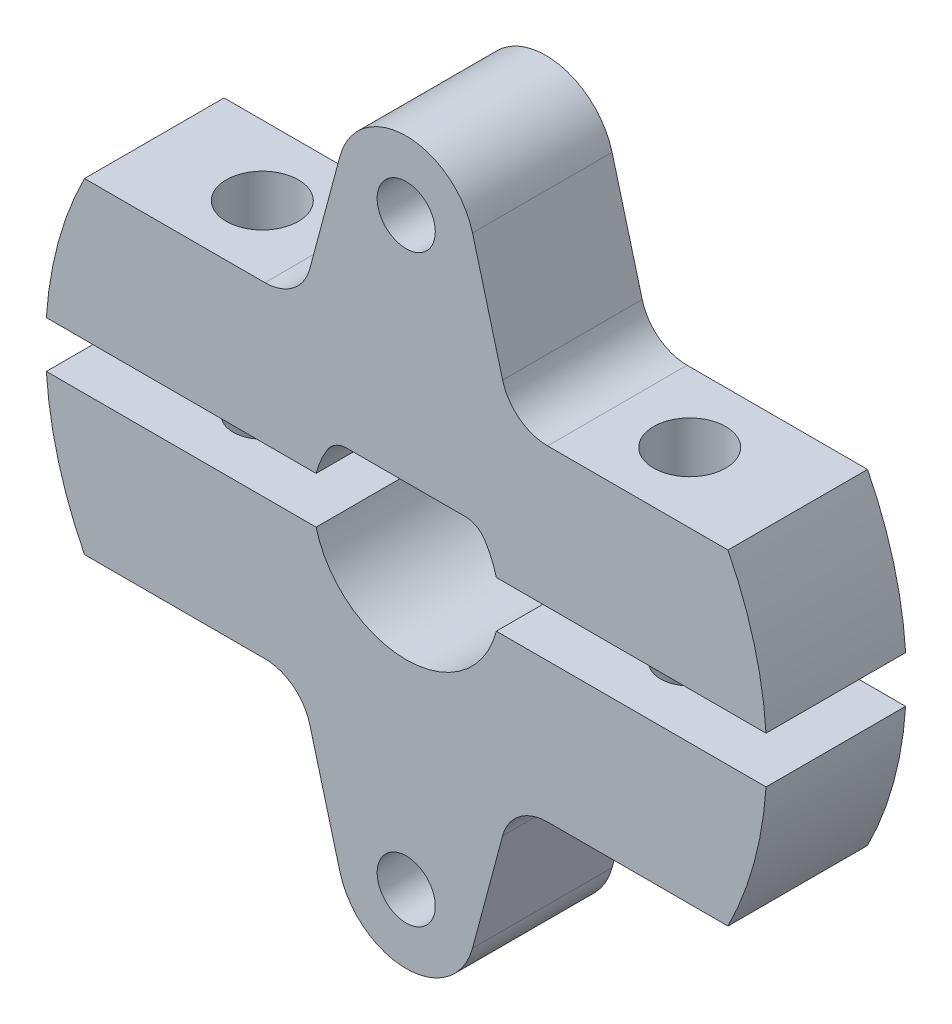
SolidWorks part; units mm, degrees
material "6061 合金"
ref_plane "前视基准面" through (0, 0, 0) normal (0, 0, 1) x (1, 0, 0)
ref_plane "上视基准面" through (0, 0, 0) normal (0, 1, 0) x (1, 0, 0)
ref_plane "右视基准面" through (0, 0, 0) normal (1, 0, 0) x (0, 0, -1)
sketch "草图1" plane through (0, 0, 0) normal (0, 0, 1) x (1, 0, 0)
  line L0 (-3.0397, 2.6) -> (3.0397, 2.6)
  arc A0 (-3.0397, 2.6) -> (3.0397, 2.6) centre (0, 0) ccw
  circle A1 centre (0, 0) radius 12.5 construction
  circle A3 centre (0, 0) radius 15.5
  dimension "D1" = 8
  dimension "D2" = 25
  dimension "D3" = 2.6
  dimension "D4" = 3
extrude "凸台-拉伸1" add sketch "草图1" along normal mid plane 6
sketch "草图2" plane through (0, 0, 3) normal (0, 0, 1) x (1, 0, 0)
  line L1 (-17.5, -1) -> (17.5, -1)
  line L2 (-17.5, -1) -> (-17.5, 1)
  line L3 (-17.5, 1) -> (17.5, 1)
  line L4 (17.5, -1) -> (17.5, 1)
  line L5 (0, 1) -> (0, -1) construction
  line L6 (-17.5, 0) -> (17.5, 0) construction
  point P0 (0, 0)
  dimension "D1" = 2
  dimension "D2" = 35
extrude "切除-拉伸1" cut sketch "草图2" against normal mid plane 48
sketch "草图3" plane through (0, 0, 3) normal (0, 0, 1) x (1, 0, 0)
  circle A0 centre (0, 0) radius 12.5 construction
  dimension "D1" = 25
hole_wizard "M3 螺纹孔1" positions "草图4" profile "草图5" tap size "M3" standard "GB" end condition through all
sketch "草图4" plane through (0, 0, 3) normal (0, 0, 1) x (1, 0, 0)
  line L0 (0, 12.55) -> (0, 0) construction
  point P0 (0, 12.55)
  dimension "D1" = 12.55
sketch "草图5" plane through (0, 12.55, 3) normal (1, 0, 0) x (0, -1, 0)
  line L0 (0, 0) -> (0, 6)
  line L1 (0, 6) -> (1.25, 6)
  line L2 (1.25, 6) -> (1.25, 0)
  line L5 (1.25, 0) -> (0, 0)
  line L11 (0, -6.35) -> (0, 107.95) construction
  dimension "通孔螺纹孔钻头直径" = 2.5
  dimension "通孔螺纹孔钻头深度" = 6
cosmetic thread "孔螺蚊线1" parameters "D2"=3
pattern_circular "阵列(圆周)1" count 2 over 360 about axis through (0, 0, 0) along (0, 0, 1) of "M3 螺纹孔1"
cosmetic thread "孔螺蚊线2" parameters "D2"=3
cosmetic thread "孔螺蚊线3" parameters "D2"=3
cosmetic thread "孔螺蚊线4" parameters "D2"=3
cosmetic thread "孔螺蚊线5" parameters "D2"=3
sketch "草图7" plane through (0, 0, 3) normal (0, 0, 1) x (1, 0, 0)
  line L0 (-13.8293, 7) -> (-4.5412, 7)
  line L1 (-4.5412, 7) -> (-2.8495, 13.3135)
  line L2 (-3.873, 1) -> (-15.4677, 1) construction
  line L3 (0, 12.55) -> (0, -12.55) construction
  line L4 (4.5412, 7) -> (2.8495, 13.3135)
  line L5 (13.8293, 7) -> (4.5412, 7)
  line L6 (0, 0) -> (15.5289, 0) construction
  line L7 (-4.5412, 7) -> (-2.8495, 13.3135)
  line L8 (4.5412, 7) -> (2.8495, 13.3135)
  line L9 (13.8293, 7) -> (4.5412, 7)
  line L10 (-13.8293, 7) -> (-4.5412, 7)
  line L11 (-13.8293, -7) -> (-4.5412, -7)
  line L12 (13.8293, -7) -> (4.5412, -7)
  line L13 (4.5412, -7) -> (2.8495, -13.3135)
  line L14 (-4.5412, -7) -> (-2.8495, -13.3135)
  line L15 (13.8293, -7) -> (4.5412, -7)
  line L16 (4.5412, -7) -> (2.8495, -13.3135)
  line L17 (-4.5412, -7) -> (-2.8495, -13.3135)
  line L18 (-13.8293, -7) -> (-4.5412, -7)
  arc A0 (2.8495, 13.3135) -> (-2.8495, 13.3135) centre (0, 12.55) ccw
  arc A1 (15.4677, 1) -> (-15.4677, 1) centre (0, 0) ccw construction
  arc A2 (13.8293, 7) -> (-13.8293, 7) centre (0, 0) ccw
  arc A3 (13.8293, -7) -> (-13.8293, -7) centre (0, 0) cw
  arc A4 (2.8495, -13.3135) -> (-2.8495, -13.3135) centre (0, -12.55) cw
  arc M7 (15.4677, 1) -> (-15.4677, 1) centre (0, 0) ccw
  dimension "D1" = 6
  dimension "D2" = 15
extrude "切除-拉伸2" cut sketch "草图7" against normal mid plane 108 contours A0 L0 L1 M7 | A0 L4 L5 M7
sketch "草图8" plane through (0, 7, 0) normal (0, 1, 0) x (1, 0, 0)
  line L0 (-9.1852, 0) -> (9.1852, 0) construction
  line L1 (9.1852, 0) -> (9.1852, 3) construction
  line L2 (13.8293, 3) -> (4.5412, 3) construction
  circle A0 centre (-9.1852, 0) radius 1.55
  circle A1 centre (9.1852, 0) radius 1.55
  point P4 (0, 0)
  dimension "D1" = 3.1
extrude "切除-拉伸3" cut sketch "草图8" against normal up to next (6 mm away)
hole_wizard "M3 螺纹孔2" positions "草图9" profile "草图10" tap size "M3" standard "GB" end condition through all
sketch "草图9" plane through (0, -1, 0) normal (0, 1, 0) x (1, 0, 0)
  point P0 (-9.1852, 0)
  point P3 (9.1852, 0)
sketch "草图10" plane through (-9.1852, -1, 0) normal (1, 0, 0) x (0, 0, 1)
  line L0 (0, 0) -> (0, 14.5)
  line L1 (0, 14.5) -> (1.25, 14.5)
  line L2 (1.25, 14.5) -> (1.25, 0)
  line L5 (1.25, 0) -> (0, 0)
  line L11 (0, -6.35) -> (0, 107.95) construction
  dimension "通孔螺纹孔钻头直径" = 2.5
  dimension "通孔螺纹孔钻头深度" = 14.5
cosmetic thread "孔螺蚊线6" parameters "D2"=3
cosmetic thread "孔螺蚊线7" parameters "D2"=3
fillet "圆角2" radius 1 2 edges at (3.0397, 2.6, 0) (-3.0397, 2.6, 0)
sketch "草图12" plane through (0, 0, 3) normal (0, 0, 1) x (1, 0, 0)
  line L0 (13.8293, -7) -> (4.5412, -7) construction
  line L1 (4.5412, -7) -> (2.8495, -13.3135) construction
  line L2 (-4.5412, -7) -> (-2.8495, -13.3135) construction
  line L3 (-13.8293, -7) -> (-4.5412, -7) construction
  line L4 (13.8293, -7) -> (4.5412, -7)
  line L5 (4.5412, -7) -> (2.8495, -13.3135)
  line L6 (-4.5412, -7) -> (-2.8495, -13.3135)
  line L7 (-13.8293, -7) -> (-4.5412, -7)
  arc A0 (-13.8293, -7) -> (13.8293, -7) centre (0, 0) ccw construction
  arc A1 (-2.8495, -13.3135) -> (2.8495, -13.3135) centre (0, -12.55) ccw construction
  arc A2 (-13.8293, -7) -> (13.8293, -7) centre (0, 0) ccw
  arc A3 (-2.8495, -13.3135) -> (2.8495, -13.3135) centre (0, -12.55) ccw
  arc M3 (-15.4677, -1) -> (15.4677, -1) centre (0, 0) ccw
extrude "切除-拉伸4" cut sketch "草图12" against normal blind 10 contours A3 L6 L7 M3 | A3 A2 L4 L5
fillet "圆角1" radius 2 2 edges at (4.5412, 7, 0) (-4.5412, 7, 0)
fillet "圆角3" radius 2 2 edges at (4.5412, -7, 0) (-4.5412, -7, 0)
